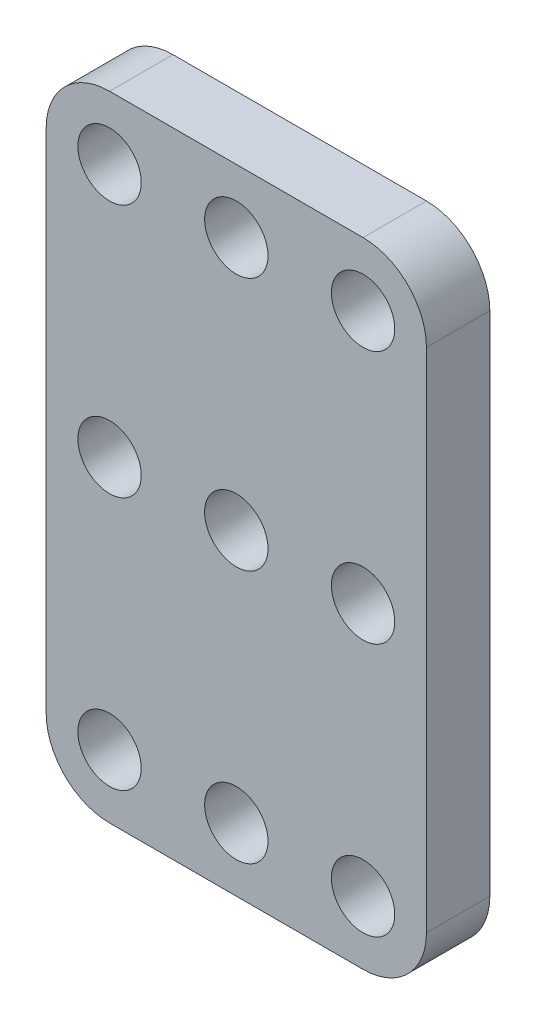
SolidWorks part; units mm, degrees
ref_plane "Ön Düzlem" through (0, 0, 0) normal (0, 0, 1) x (1, 0, 0)
ref_plane "Üst Düzlem" through (0, 0, 0) normal (0, 1, 0) x (1, 0, 0)
ref_plane "Sağ Düzlem" through (0, 0, 0) normal (1, 0, 0) x (0, 0, -1)
sketch "Çizim1" plane through (0, 0, 0) normal (0, 0, 1) x (1, 0, 0)
  line L1 (-64.0963, 22.8333) -> (-34.0963, 22.8333)
  line L2 (-64.0963, 22.8333) -> (-64.0963, -27.1667)
  line L3 (-64.0963, -27.1667) -> (-34.0963, -27.1667)
  line L4 (-34.0963, 22.8333) -> (-34.0963, -27.1667)
  circle A0 centre (-59.0963, 17.8333) radius 2.5
  circle A1 centre (-49.0963, 17.8333) radius 2.5
  circle A2 centre (-39.0963, 17.8333) radius 2.5
  circle A3 centre (-49.0963, -2.1667) radius 2.5
  circle A4 centre (-39.0963, -2.1667) radius 2.5
  circle A5 centre (-49.0963, -22.1667) radius 2.5
  circle A6 centre (-39.0963, -22.1667) radius 2.5
  circle A7 centre (-59.0963, -2.1667) radius 2.5
  circle A8 centre (-59.0963, -22.1667) radius 2.5
  dimension "D3" = 5
  dimension "D4" = 5
  dimension "D5" = 5
  dimension "D1" = 30
  dimension "D2" = 50
  dimension "D6" = 3
  dimension "D7" = 3
extrude "Yükseklik-Ekstrüzyon1" add sketch "Çizim1" along normal blind 5
fillet "Radyus1" radius 5 4 edges at (-64.0963, 22.8333, 2.5) (-64.0963, -27.1667, 2.5) (-34.0963, 22.8333, 2.5) (-34.0963, -27.1667, 2.5)
